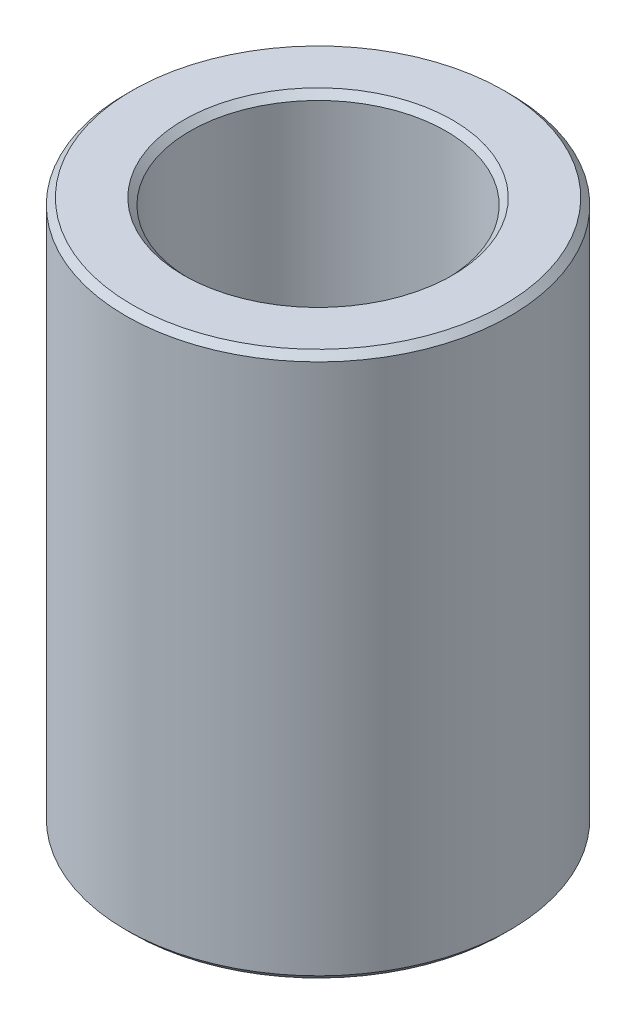
SolidWorks part; units mm, degrees
ref_plane "Front Plane" through (0, 0, 0) normal (0, 0, 1) x (1, 0, 0)
ref_plane "Top Plane" through (0, 0, 0) normal (0, 1, 0) x (1, 0, 0)
ref_plane "Right Plane" through (0, 0, 0) normal (1, 0, 0) x (0, 0, -1)
sketch "Sketch1" plane through (0, 0, 0) normal (0, 1, 0) x (1, 0, 0)
  circle A0 centre (0, 0) radius 4
  circle A1 centre (0, 0) radius 6
  dimension "D1" = 8
  dimension "D2" = 2
extrude "Boss-Extrude1" add sketch "Sketch1" along normal blind 17
chamfer "Chamfer1" distance 0.2 angle 45 4 edges at (0, 0, 6) (0, 17, 6) (0, 0, 4) (0, 17, 4)
